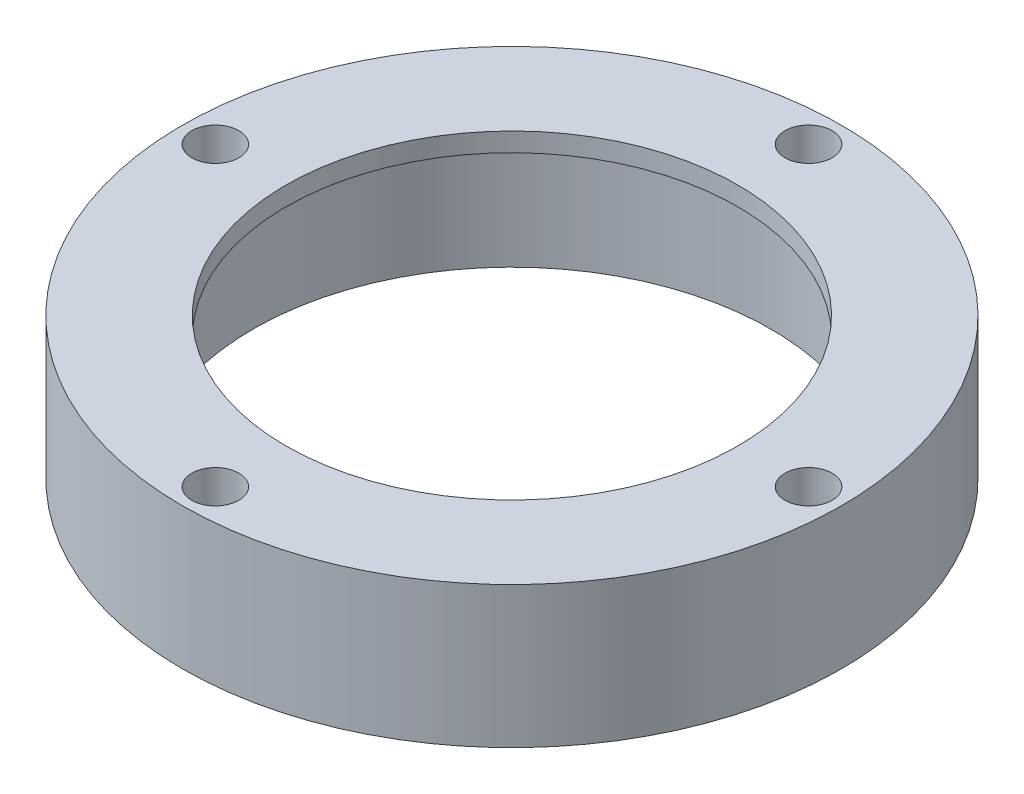
SolidWorks part; units mm, degrees
ref_plane "Спереди" through (0, 0, 0) normal (0, 0, 1) x (1, 0, 0)
ref_plane "Сверху" through (0, 0, 0) normal (0, 1, 0) x (1, 0, 0)
ref_plane "Справа" through (0, 0, 0) normal (1, 0, 0) x (0, 0, -1)
sketch "Эскиз1" plane through (0, 0, 0) normal (0, 0, 1) x (1, 0, 0)
  line L0 (0, 60.6098) -> (0, -86.1926) construction
  line L1 (24, 14.7849) -> (35, 14.7849)
  line L2 (35, 14.7849) -> (35, -0.2151)
  line L3 (35, -0.2151) -> (27.5, -0.2151)
  line L4 (27.5, -0.2151) -> (27.5, 12.7849)
  line L5 (27.5, 12.7849) -> (24, 12.7849)
  line L6 (24, 12.7849) -> (24, 14.7849)
  dimension "D1" = 35
  dimension "D2" = 27.5
  dimension "D3" = 13
  dimension "D4" = 24
  dimension "D5" = 2
revolve "Повернуть1" add sketch "Эскиз1" angle 360 about L0
sketch "Эскиз2" plane through (0, -0.2151, 0) normal (0, -1, 0) x (1, 0, 0)
  circle A0 centre (0, 0) radius 31.5 construction
  circle A1 centre (0, 31.5) radius 2.5
  circle A2 centre (0, -31.5) radius 2.5
  circle A3 centre (31.5, 0) radius 2.5
  circle A4 centre (-31.5, 0) radius 2.5
  dimension "D1" = 63
  dimension "D2" = 5
  dimension "D3" = 5
  dimension "D4" = 5
  dimension "D5" = 5
extrude "Вырез-Вытянуть1" cut sketch "Эскиз2" against normal blind 22
